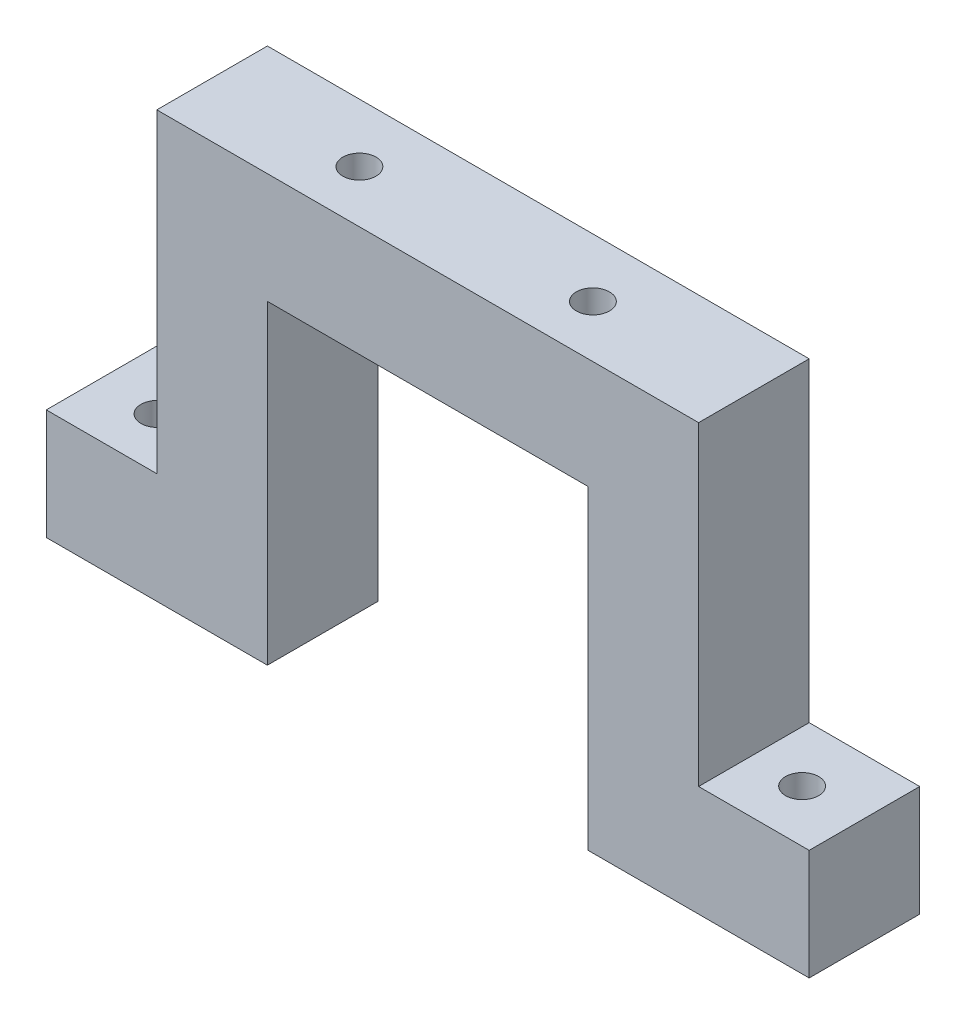
SolidWorks part; units mm, degrees
ref_plane "Front Plane" through (0, 0, 0) normal (0, 0, 1) x (1, 0, 0)
ref_plane "Top Plane" through (0, 0, 0) normal (0, 1, 0) x (1, 0, 0)
ref_plane "Right Plane" through (0, 0, 0) normal (1, 0, 0) x (0, 0, -1)
sketch "Sketch1" plane through (0, 0, 0) normal (0, 0, 1) x (1, 0, 0)
  line L0 (0, 0) -> (10, 0)
  line L1 (10, 0) -> (10, 28.5)
  line L2 (10, 28.5) -> (59, 28.5)
  line L3 (59, 28.5) -> (59, 0)
  line L4 (59, 0) -> (69, 0)
  dimension "D1" = 10
  dimension "D2" = 28.5
  dimension "D3" = 10
  dimension "D4" = 49
extrude "Extrude-Thin1" add sketch "Sketch1" along normal blind 10 thin
sketch "Sketch2" plane through (0, 0, 0) normal (0, 1, 0) x (1, 0, 0)
  line L0 (0, -10) -> (0, 0) construction
  line L1 (0, 0) -> (10, 0) construction
  line L2 (69, -10) -> (69, 0) construction
  line L3 (59, 0) -> (69, 0) construction
  circle A0 centre (5.3479, -5.2871) radius 1.5
  circle A1 centre (63.65, -5.2871) radius 1.5
  circle A2 centre (23.61, -5.2871) radius 1.5
  circle A3 centre (44.7257, -5.2871) radius 1.5
  dimension "D1" = 3
  dimension "D3" = 5.2871
  dimension "D4" = 3
  dimension "D7" = 3
  dimension "D8" = 3
  dimension "D2" = 5.3479
  dimension "D5" = 5.35
  dimension "D6" = 5.2871
extrude "Cut-Extrude1" cut sketch "Sketch2" along normal blind 38 and the other way blind 45
